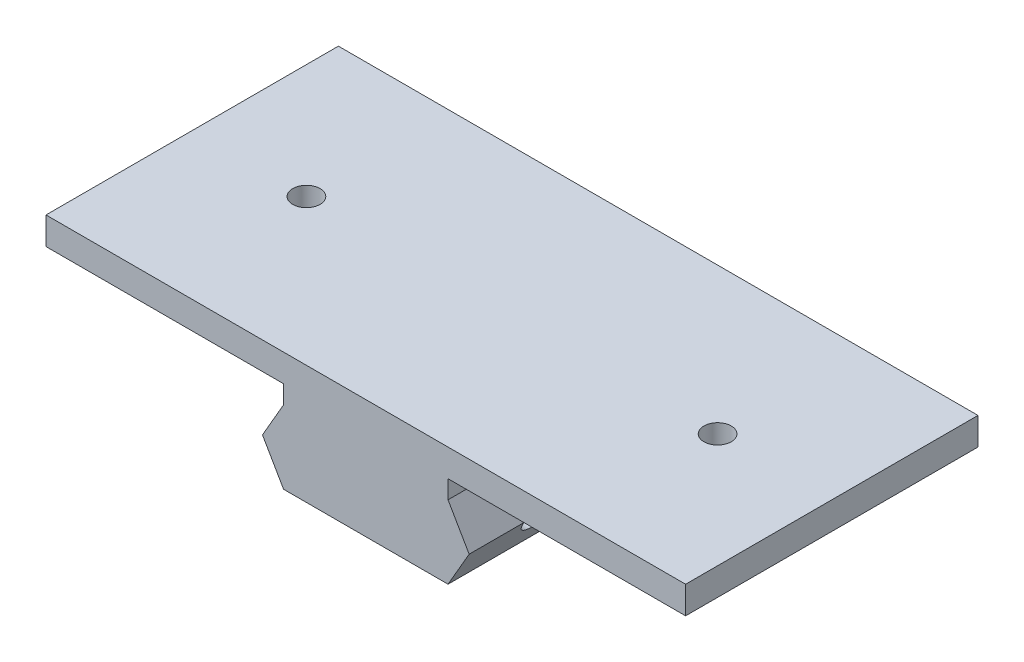
SolidWorks part; units mm, degrees
ref_plane "Front Plane" through (0, 0, 0) normal (0, 0, 1) x (1, 0, 0)
ref_plane "Top Plane" through (0, 0, 0) normal (0, 1, 0) x (1, 0, 0)
ref_plane "Right Plane" through (0, 0, 0) normal (1, 0, 0) x (0, 0, -1)
sketch "Sketch1" plane through (0, 0, 0) normal (0, 0, 1) x (1, 0, 0)
  line L0 (9, 0) -> (-9, 0)
  line L1 (-9, 0) -> (-11.3094, 4)
  line L2 (-11.3094, 4) -> (-9, 8)
  line L3 (-9, 8) -> (9, 8)
  line L4 (9, 8) -> (11.3094, 4)
  line L5 (11.3094, 4) -> (9, 0)
  dimension "D1" = 18
  dimension "D2" = 120
  dimension "D3" = 120
  dimension "D4" = 120
  dimension "D5" = 120
  dimension "D6" = 8
extrude "Boss-Extrude1" add sketch "Sketch1" along normal blind 32
sketch "Sketch2" plane through (0, 0, 0) normal (1, 0, 0) x (0, 0, -1)
  line L0 (-32, 4) -> (0, 4) construction
  line L1 (-32, 4) -> (-32, 8) construction
  circle A0 centre (-24, 4) radius 2
  dimension "D1" = 4
  dimension "D2" = 8
extrude "Cut-Extrude1" cut sketch "Sketch2" against normal through all both and the other way through all contours A0
pattern_linear "LPattern1" count 3 spacing 8 along (0, 0, -1) of "Cut-Extrude1"
sketch "Sketch3" plane through (0, 0, 0) normal (1, 0, 0) x (0, 0, -1)
  line L1 (-32, 8) -> (0, 8)
  line L2 (-32, 8) -> (-32, 10)
  line L3 (-32, 10) -> (0, 10)
  line L4 (0, 8) -> (0, 10)
  line L5 (-32, 8) -> (0, 10) construction
  line L6 (-32, 10) -> (0, 8) construction
  point P4 (-16, 9)
  dimension "D1" = 2
extrude "Boss-Extrude2" add sketch "Sketch3" along normal up to vertex (9 mm away) and the other way up to vertex (9 mm away) up to point (9, 8, 32) other way up to point (-9, 8, 32)
sketch "Sketch4" plane through (0, 0, 0) normal (1, 0, 0) x (0, 0, -1)
  line L1 (-32, 10) -> (0, 10)
  line L2 (-32, 10) -> (-32, 13)
  line L3 (-32, 13) -> (0, 13)
  line L4 (0, 10) -> (0, 13)
  line L5 (-32, 10) -> (0, 13) construction
  line L6 (-32, 13) -> (0, 10) construction
  point P4 (-16, 11.5)
  dimension "D1" = 3
extrude "Boss-Extrude3" add sketch "Sketch4" along normal blind 35 and the other way blind 35
sketch "Sketch5" plane through (0, 13, 0) normal (0, 1, 0) x (1, 0, 0)
  line L0 (0, -16) -> (22.5, -16) construction
  line L1 (-22.5, -16) -> (0, -16) construction
  line L3 (0, 0) -> (0, -32) construction
  line L6 (-35, -32) -> (35, -32) construction
  circle A0 centre (-22.5, -16) radius 1.5
  circle A1 centre (22.5, -16) radius 1.5
  dimension "D3" = 3
  dimension "D1" = 22.5
extrude "Cut-Extrude2" cut sketch "Sketch5" against normal blind 10
